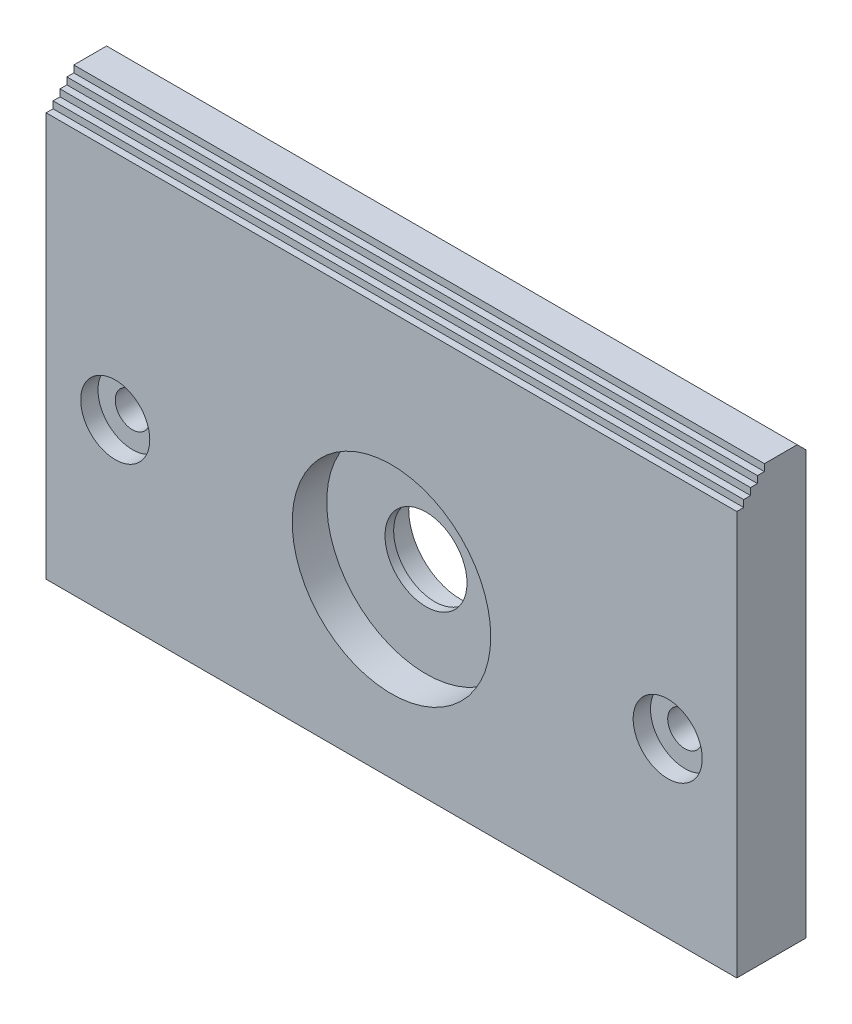
SolidWorks part; units mm, degrees
ref_plane "前视基准面" through (0, 0, 0) normal (0, 0, 1) x (1, 0, 0)
ref_plane "上视基准面" through (0, 0, 0) normal (0, 1, 0) x (1, 0, 0)
ref_plane "右视基准面" through (0, 0, 0) normal (1, 0, 0) x (0, 0, -1)
other "Configuration Table"
ref_plane "基准面1" through (0, 0, 8) normal (0, 0, 1) x (1, 0, 0)
sketch "草图1" plane through (0, 0, 8) normal (0, 0, 1) x (1, 0, 0)
  line L0 (80, -19.1667) -> (80, 40.8333)
  line L1 (80, 40.8333) -> (0, 40.8333)
  line L2 (0, 40.8333) -> (0, -19.1667)
  line L3 (0, -19.1667) -> (80, -19.1667)
  dimension "D1" = 80
  dimension "D2" = 60
extrude "凸台-拉伸1" add sketch "草图1" against normal blind 8
hole_wizard "M3.5 六角头机械螺钉的柱形沉头孔1" positions "草图13" profile "草图12" counterbore size "M3.5" standard "ANSI Metric" end condition through all
sketch "草图13" plane through (0, 0, 8) normal (0, 0, 1) x (1, 0, 0)
  line L1 (0, 10.8333) -> (80, 10.8333) construction
  line L2 (0, 40.8333) -> (0, -19.1667) construction
  line L3 (80, -19.1667) -> (80, 40.8333) construction
  point P0 (8, 10.8333)
  point P1 (72, 10.8333)
  dimension "D1" = 8
  dimension "D2" = 8
sketch "草图12" plane through (8, 10.8333, 8) normal (1, 0, 0) x (0, -1, 0)
  line L0 (0, 0) -> (0, 8)
  line L1 (0, 8) -> (2, 8)
  line L3 (2, 8) -> (2, 2)
  line L4 (2, 2) -> (4, 2)
  line L5 (4, 2) -> (4, 0)
  line L7 (4, 0) -> (0, 0)
  line L11 (0, -6.35) -> (0, 107.95) construction
  dimension "通孔孔直径" = 4
  dimension "通孔孔深度" = 8
  dimension "柱形沉头孔直径" = 8
  dimension "柱形沉头孔深度" = 2
sketch "草图14" plane through (0, 0, 8) normal (0, 0, 1) x (1, 0, 0)
  line L0 (40, 40.8333) -> (40, -19.1667) construction
  line L1 (80, 40.8333) -> (0, 40.8333) construction
  line L2 (0, -19.1667) -> (80, -19.1667) construction
  line L3 (0, 40.8333) -> (0, -19.1667) construction
  line L4 (0, 38.8333) -> (80, 38.8333)
  line L5 (0, 38.8333) -> (0, 36.8333)
  line L6 (0, 36.8333) -> (80, 36.8333)
  line L7 (40, 38.8333) -> (40, 36.8333)
  line L8 (80, -19.1667) -> (80, 40.8333) construction
  line L9 (15, 40.8333) -> (31, 24.8333)
  line L10 (6, 40.8333) -> (8, 40.8333)
  line L11 (6, 40.8333) -> (6, 24.8333)
  line L12 (6, 24.8333) -> (8, 24.8333)
  line L13 (8, 40.8333) -> (8, 24.8333)
  line L18 (39, 40.8333) -> (41, 40.8333)
  line L19 (39, 40.8333) -> (39, 24.8333)
  line L20 (39, 24.8333) -> (41, 24.8333)
  line L21 (40, 40.8333) -> (40, 24.8333)
  line L22 (31, 24.8333) -> (32.4142, 26.2475)
  line L23 (32.4142, 26.2475) -> (16.4142, 42.2475)
  line L24 (16.4142, 42.2475) -> (15, 40.8333)
  line L25 (0, 24.8333) -> (80, 24.8333) construction
  line L26 (74, 24.8333) -> (72, 24.8333)
  line L27 (72, 40.8333) -> (72, 24.8333)
  line L28 (74, 40.8333) -> (72, 40.8333)
  line L29 (74, 40.8333) -> (74, 24.8333)
  line L30 (47.5858, 26.2475) -> (63.5858, 42.2475)
  line L31 (49, 24.8333) -> (47.5858, 26.2475)
  line L32 (65, 40.8333) -> (49, 24.8333)
  line L33 (63.5858, 42.2475) -> (65, 40.8333)
  line L34 (41, 40.8333) -> (41, 24.8333)
  line L35 (80, 38.8333) -> (80, 36.8333)
  dimension "D1" = 2
  dimension "D2" = 2
  dimension "D3" = 6
  dimension "D4" = 2
  dimension "D5" = 16
  dimension "D6" = 2
  dimension "D7" = 1
  dimension "D8" = 7
  dimension "D9" = 45
extrude "切除-拉伸1" cut sketch "草图14" against normal blind 1 contours L4 L35 L6 L5 | L13 L12 L11 L10 | L9 L22 L23 L24 | L19 L20 L34 L18 | L30 L33 L32 L31 | L27 L26 L29 L28
sketch "草图15" plane through (0, 0, 8) normal (0, 0, 1) x (1, 0, 0)
  line L0 (40, 40.8333) -> (40, -19.1667) construction
  line L1 (39, 40.8333) -> (41, 40.8333) construction
  line L2 (0, -19.1667) -> (80, -19.1667) construction
  circle A0 centre (40, 10.8333) radius 4.75
  point P9 (40, 10.8333)
  dimension "D1" = 9.5
extrude "切除-拉伸2" cut sketch "草图15" against normal up to next
sketch "草图17" plane through (0, 0, 8) normal (0, 0, 1) x (1, 0, 0)
  circle A0 centre (40, 10.8333) radius 11.5
  dimension "D1" = 23
extrude "切除-拉伸4" cut sketch "草图17" against normal blind 4
sketch "草图18" plane through (0, 0, 0) normal (0, 0, -1) x (-1, 0, 0)
  circle A0 centre (-40, 10.8333) radius 6
  dimension "D1" = 12
extrude "切除-拉伸5" cut sketch "草图18" against normal blind 3
chamfer "倒角1" distance 1.5 angle 45 2 edges at (74, 10.8333, 0) (10, 10.8333, 0)
chamfer "倒角2" distance 1 angle 45 1 edges at (40, 40.8333, 0)
sketch "草图20" plane through (0, 0, 8) normal (0, 0, 1) x (1, 0, 0)
  line L0 (80, -19.1667) -> (80, 36.8333) construction
  line L1 (0, -19.1667) -> (80, -19.1667)
  line L2 (0, -19.1667) -> (0, -13.1667)
  line L3 (0, -13.1667) -> (80, -13.1667)
  line L4 (80, -19.1667) -> (80, -13.1667)
  dimension "D1" = 6
extrude "切除-拉伸6" cut sketch "草图20" against normal blind 1
sketch "草图21" plane through (0, 0, 7) normal (0, 0, 1) x (1, 0, 0)
  line L0 (80, -19.1667) -> (80, -13.1667) construction
  line L1 (0, -19.1667) -> (80, -19.1667)
  line L2 (0, -19.1667) -> (0, -15.1667)
  line L3 (0, -15.1667) -> (80, -15.1667)
  line L4 (80, -19.1667) -> (80, -15.1667)
  dimension "D1" = 4
extrude "切除-拉伸7" cut sketch "草图21" against normal blind 1
sketch "草图22" plane through (0, 0, 6) normal (0, 0, 1) x (1, 0, 0)
  line L1 (0, -19.1667) -> (80, -19.1667)
  line L2 (0, -19.1667) -> (0, -17.1667)
  line L3 (0, -17.1667) -> (80, -17.1667)
  line L4 (80, -19.1667) -> (80, -17.1667)
  dimension "D1" = 2
extrude "切除-拉伸8" cut sketch "草图22" against normal blind 1
sketch "草图23" plane through (0, 0, 8) normal (0, 0, 1) x (1, 0, 0)
  line L0 (6, 24.8333) -> (8, 24.8333) construction
  line L1 (31, 24.8333) -> (32.4142, 26.2475) construction
  line L2 (39, 24.8333) -> (41, 24.8333) construction
  line L3 (49, 24.8333) -> (47.5858, 26.2475) construction
  line L4 (74, 24.8333) -> (72, 24.8333) construction
  circle A0 centre (7, 24.8333) radius 1
  circle A1 centre (31.7071, 25.5404) radius 1
  circle A2 centre (40, 24.8333) radius 1
  circle A3 centre (48.2929, 25.5404) radius 1
  circle A4 centre (73, 24.8333) radius 1
extrude "切除-拉伸9" cut sketch "草图23" against normal up to surface (1 mm away) up to face at (40, 35.6249, 7)
sketch "草图24" plane through (0, 0, 8) normal (0, 0, 1) x (1, 0, 0)
  line L0 (0, 36.8333) -> (0, -13.1667) construction
  line L1 (0, -9.1667) -> (80, -9.1667)
  line L2 (0, -9.1667) -> (0, -19.1667)
  line L3 (0, -19.1667) -> (80, -19.1667)
  line L4 (80, -9.1667) -> (80, -19.1667)
  dimension "D1" = 10
extrude "切除-拉伸10" cut sketch "草图24" against normal up to next
sketch "草图25" plane through (0, 0, 8) normal (0, 0, 1) x (1, 0, 0)
  line L0 (80, -9.1667) -> (80, 36.8333) construction
  line L1 (0, 40.8333) -> (80, 40.8333)
  line L2 (0, 40.8333) -> (0, 22.8333)
  line L3 (0, 22.8333) -> (80, 22.8333)
  line L4 (80, 40.8333) -> (80, 22.8333)
  line L5 (0, 36.8333) -> (0, -9.1667) construction
  dimension "D1" = 18
extrude "凸台-拉伸2" add sketch "草图25" against normal blind 3
sketch "草图26" plane through (0, 0, 0) normal (-1, 0, 0) x (0, 0, 1)
  line L0 (4.8, 40.8333) -> (4.8, 40.0333)
  line L1 (1, 40.8333) -> (8, 40.8333) construction
  line L2 (4.8, 40.0333) -> (5.6, 40.0333)
  line L3 (5.6, 40.0333) -> (5.6, 39.2333)
  line L4 (5.6, 39.2333) -> (6.4, 39.2333)
  line L5 (6.4, 39.2333) -> (6.4, 38.4333)
  line L6 (6.4, 38.4333) -> (7.2, 38.4333)
  line L7 (7.2, 38.4333) -> (7.2, 37.6333)
  line L8 (7.2, 37.6333) -> (8, 37.6333)
  line L9 (8, 40.8333) -> (8, -9.1667) construction
  line L10 (8, 37.6333) -> (8, 40.8333)
  line L11 (8, 40.8333) -> (4.8, 40.8333)
  dimension "D1" = 0.8
  dimension "D2" = 0.8
  dimension "D3" = 0.8
  dimension "D4" = 0.8
  dimension "D5" = 0.8
  dimension "D6" = 0.8
  dimension "D7" = 0.8
  dimension "D8" = 0.8
extrude "切除-拉伸11" cut sketch "草图26" against normal up to next
